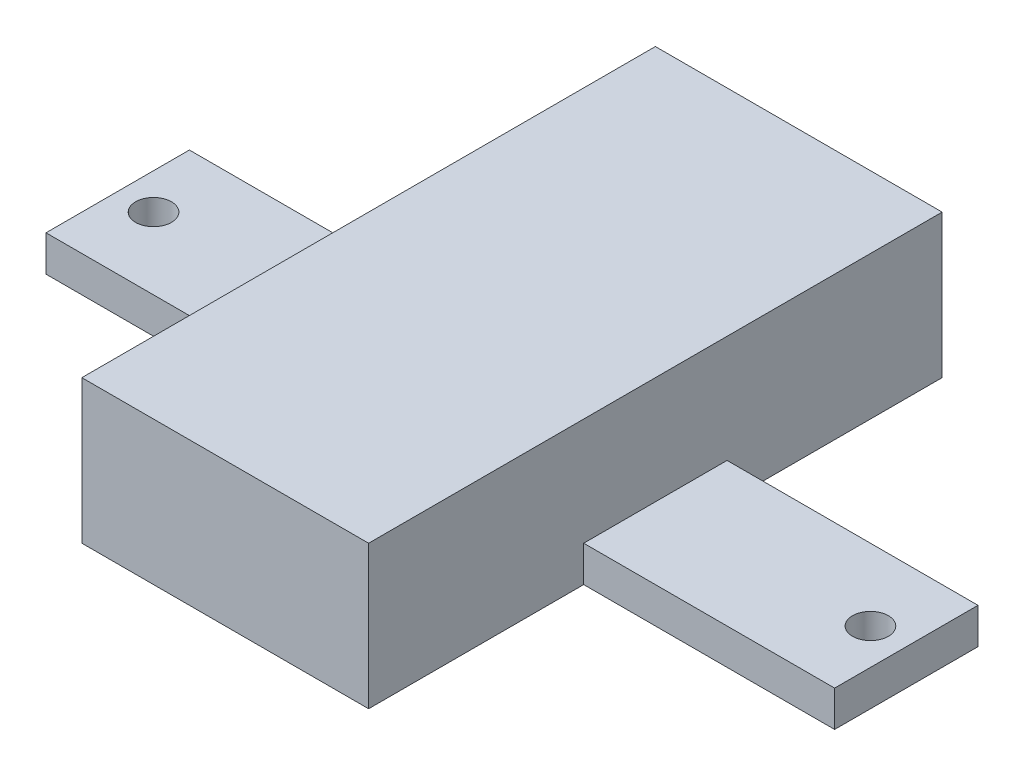
SolidWorks part; units mm, degrees
ref_plane "Front Plane" through (0, 0, 0) normal (0, 0, 1) x (1, 0, 0)
ref_plane "Top Plane" through (0, 0, 0) normal (0, 1, 0) x (1, 0, 0)
ref_plane "Right Plane" through (0, 0, 0) normal (1, 0, 0) x (0, 0, -1)
sketch "Sketch2" plane through (0, 0, 0) normal (0, 0, 1) x (1, 0, 0)
  line L1 (-34.925, 1.5875) -> (34.925, 1.5875)
  line L2 (-34.925, 1.5875) -> (-34.925, -1.5875)
  line L3 (-34.925, -1.5875) -> (34.925, -1.5875)
  line L4 (34.925, 1.5875) -> (34.925, -1.5875)
  line L5 (-34.925, 1.5875) -> (34.925, -1.5875) construction
  line L6 (-34.925, -1.5875) -> (34.925, 1.5875) construction
  point P0 (0, 0)
  point P6 (0, 0)
  point P7 (0, 0)
  point P8 (0, 0)
  point P9 (0, 0)
  point P10 (0, 0)
  dimension "D1" = 69.85
  dimension "D2" = 3.175
extrude "Boss-Extrude1" add sketch "Sketch2" against normal mid plane 12.7
sketch "Sketch5" plane through (0, 0, 0) normal (0, 0, 1) x (1, 0, 0)
  line L0 (0, -1.5875) -> (0, 1.5875) construction
  line L1 (-34.925, -1.5875) -> (34.925, -1.5875) construction
  line L2 (34.925, 1.5875) -> (-34.925, 1.5875) construction
  line L3 (0, 11.1125) -> (0, 9.8918) construction
  line L4 (-12.7, -1.5875) -> (12.7, -1.5875)
  line L5 (-12.7, -1.5875) -> (-12.7, 11.1125)
  line L6 (-12.7, 11.1125) -> (12.7, 11.1125)
  line L7 (12.7, -1.5875) -> (12.7, 11.1125)
  point P10 (0, 11.1125)
  dimension "D1" = 25.4
  dimension "D2" = 12.7
extrude "Boss-Extrude2" add sketch "Sketch5" along normal mid plane 50.8
sketch "Sketch6" plane through (0, 1.5875, 0) normal (0, 1, 0) x (1, 0, 0)
  line L0 (-34.925, 0) -> (34.925, 0) construction
  line L1 (-34.925, 6.35) -> (-34.925, -6.35) construction
  line L2 (34.925, 6.35) -> (34.925, -6.35) construction
  line L3 (0, 0) -> (0, 11.5563) construction
  circle A0 centre (-31.75, 0) radius 1.5875
  circle A1 centre (31.75, 0) radius 1.5875
  dimension "D1" = 3.175
  dimension "D2" = 3.175
extrude "Cut-Extrude1" cut sketch "Sketch6" against normal through all
